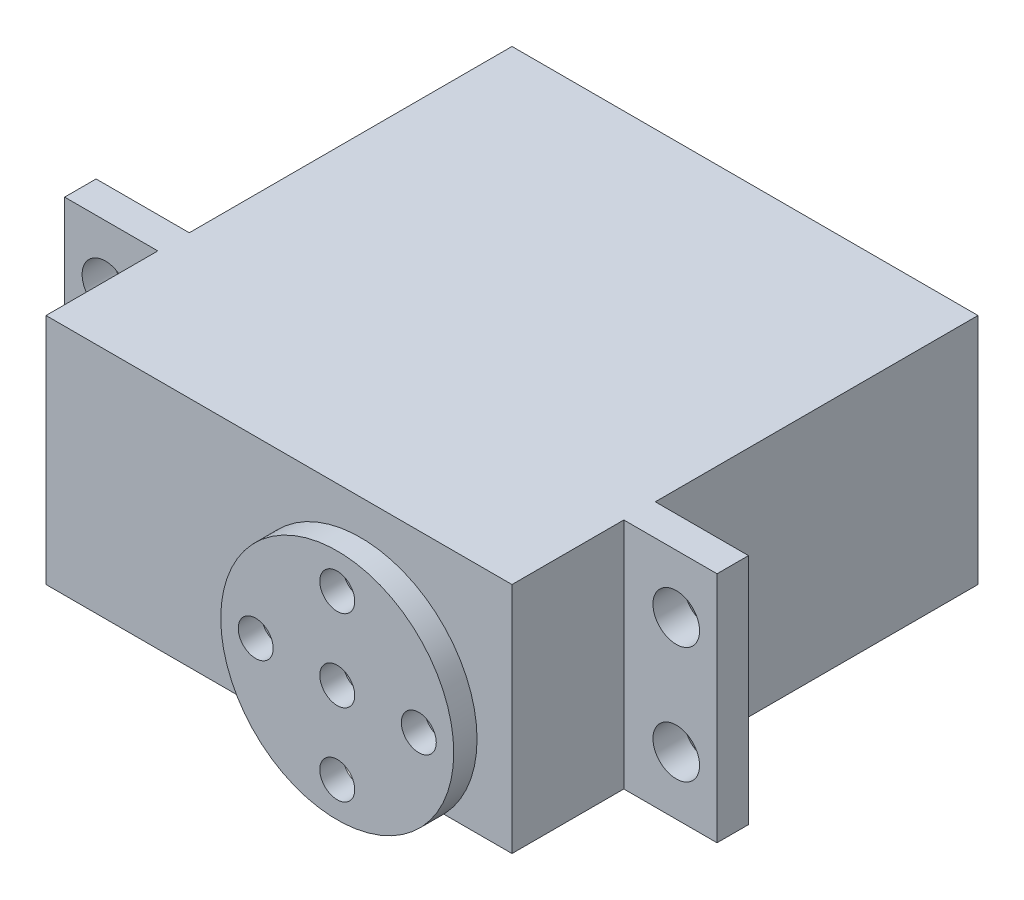
SolidWorks part; units mm, degrees
material "ABS"
ref_plane "前视基准面" through (0, 0, 0) normal (0, 0, 1) x (1, 0, 0)
ref_plane "上视基准面" through (0, 0, 0) normal (0, 1, 0) x (1, 0, 0)
ref_plane "右视基准面" through (0, 0, 0) normal (1, 0, 0) x (0, 0, -1)
sketch "草图1" plane through (0, 0, 0) normal (0, 0, 1) x (1, 0, 0)
  line L0 (-40, 20) -> (0, 20)
  line L1 (0, 20) -> (0, 0)
  line L2 (0, 0) -> (-40, 0)
  line L3 (-40, 0) -> (-40, 20)
  dimension "D1" = 40
  dimension "D2" = 20
extrude "凸台-拉伸1" add sketch "草图1" along normal blind 27.7
sketch "草图2" plane through (0, 0, 27.7) normal (0, 0, 1) x (1, 0, 0)
  line L1 (-48, 20) -> (8, 20)
  line L2 (-48, 20) -> (-48, 0)
  line L3 (-48, 0) -> (8, 0)
  line L4 (8, 20) -> (8, 0)
  line L7 (-40, 20) -> (-40, 0) construction
  line L8 (-20, 15) -> (-20, 20) construction
  line L9 (-44.5, 15) -> (4.5, 15) construction
  line L10 (-44.5, 15) -> (-44.5, 5) construction
  line L11 (-44.5, 5) -> (4.5, 5) construction
  line L12 (4.5, 15) -> (4.5, 5) construction
  line L13 (-44.5, 10) -> (-48, 10) construction
  circle A0 centre (-44.5, 15) radius 2
  circle A1 centre (-44.5, 5) radius 2
  circle A2 centre (4.5, 15) radius 2
  circle A3 centre (4.5, 5) radius 2
  dimension "D3" = 10
  dimension "D5" = 4
  dimension "D1" = 56
  dimension "D2" = 8
  dimension "D4" = 49
extrude "凸台-拉伸2" add sketch "草图2" along normal blind 2.7
sketch "草图5" plane through (0, 0, 0) normal (0, 0, -1) x (-1, 0, 0)
  line L1 (0, 20) -> (40, 20)
  line L2 (0, 20) -> (0, 0)
  line L3 (0, 0) -> (40, 0)
  line L4 (40, 20) -> (40, 0)
extrude "凸台-拉伸3" add sketch "草图5" against normal blind 40
sketch "草图6" plane through (0, 0, 40) normal (0, 0, 1) x (1, 0, 0)
  line L0 (-40, 10) -> (-10, 10) construction
  line L1 (-40, 0) -> (-40, 20) construction
  line L2 (0, 0) -> (0, 20) construction
  circle A0 centre (-10, 10) radius 3
  dimension "D1" = 10
  dimension "D2" = 6
extrude "凸台-拉伸4" add sketch "草图6" along normal blind 4.5
sketch "草图7" plane through (0, 0, 44.5) normal (0, 0, 1) x (1, 0, 0)
  circle A0 centre (-10, 10) radius 10
extrude "凸台-拉伸5" add sketch "草图7" along normal blind 0.5 and the other way blind 1.5
sketch "草图8" plane through (0, 0, 45) normal (0, 0, 1) x (1, 0, 0)
  circle A0 centre (-10, 10) radius 1.5
  circle A1 centre (-3, 10) radius 1.5
  circle A2 centre (-10, 17) radius 1.5
  circle A3 centre (-10, 3) radius 1.5
  circle A4 centre (-10, 10) radius 10 construction
  circle A5 centre (-10, 10) radius 7 construction
  circle A6 centre (-17, 10) radius 1.5
  point P17 (-10, 10)
  dimension "D1" = 3
  dimension "D3" = 7
  dimension "D4" = 3
  dimension "D2" = 4
extrude "切除-拉伸4" cut sketch "草图8" against normal up to surface (2 mm away) up to face at (-7, 10, 43)
